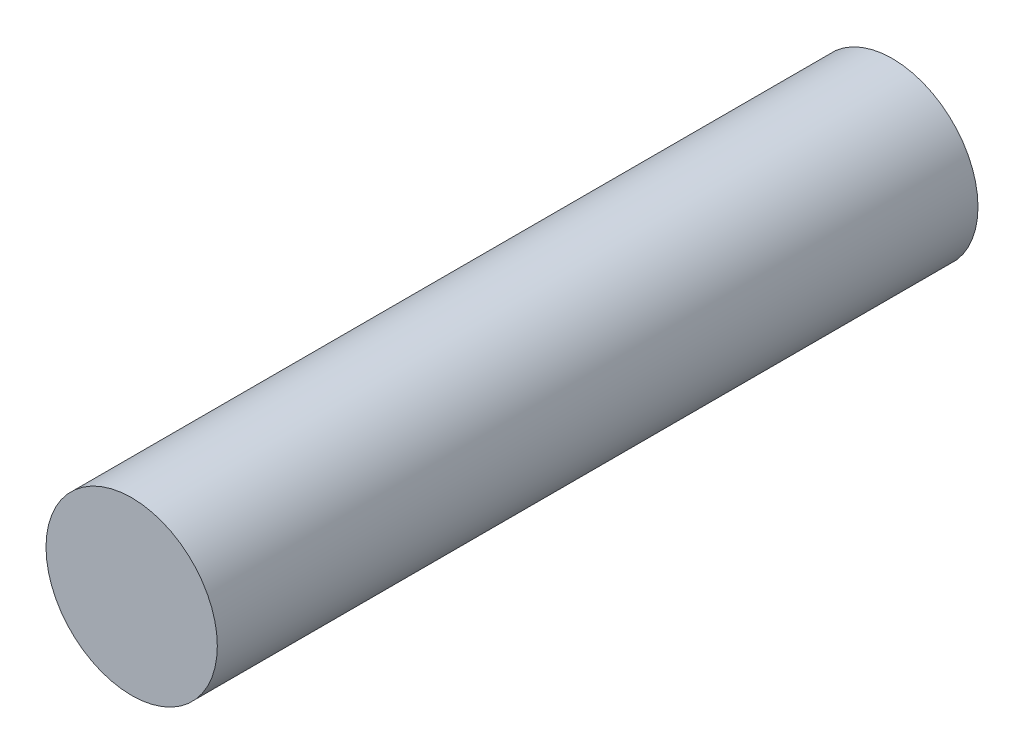
SolidWorks part; units mm, degrees
ref_plane "Front Plane" through (0, 0, 0) normal (0, 0, 1) x (1, 0, 0)
ref_plane "Top Plane" through (0, 0, 0) normal (0, 1, 0) x (1, 0, 0)
ref_plane "Right Plane" through (0, 0, 0) normal (1, 0, 0) x (0, 0, -1)
sketch "Sketch1" plane through (0, 0, 0) normal (0, 0, 1) x (1, 0, 0)
  circle A0 centre (0, 0) radius 0.75
  dimension "D1" = 1.5
extrude "Boss-Extrude1" add sketch "Sketch1" along normal blind 6.66
equation "\"D1@Boss-Extrude1\"=5.16+1.5"
